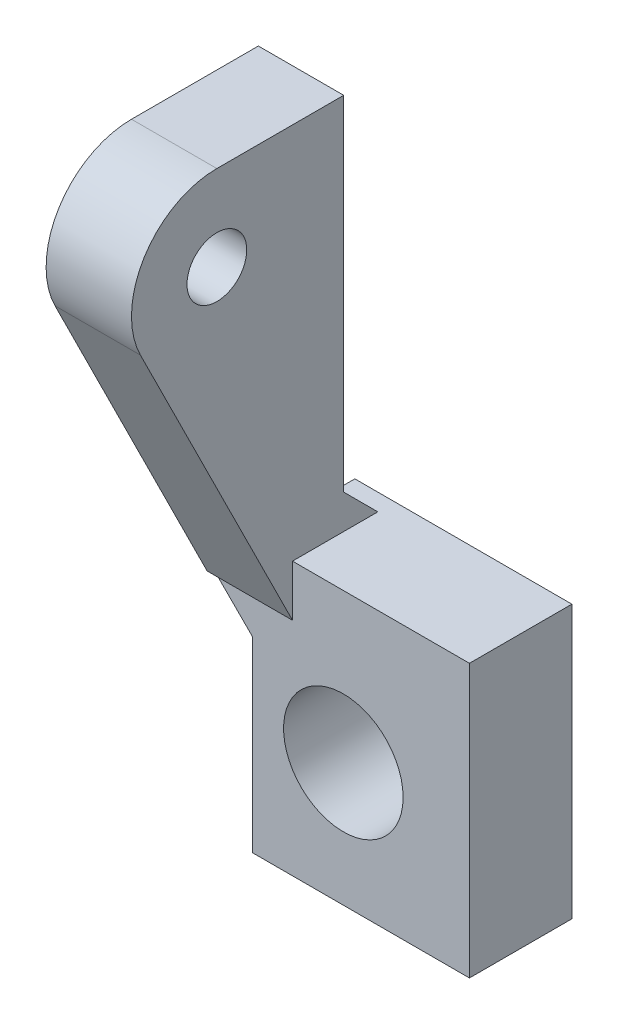
SolidWorks part; units mm, degrees
ref_plane "Front Plane" through (0, 0, 0) normal (0, 0, 1) x (1, 0, 0)
ref_plane "Top Plane" through (0, 0, 0) normal (0, 1, 0) x (1, 0, 0)
ref_plane "Right Plane" through (0, 0, 0) normal (1, 0, 0) x (0, 0, -1)
sketch "Sketch1" plane through (0, 0, 46.4115) normal (0, 0, 1) x (1, 0, 0)
  line L5 (33.1528, -0.655) -> (45.8638, -0.655)
  line L6 (33.1528, -0.655) -> (33.1528, 15.3086)
  line L7 (33.1528, 15.3086) -> (45.8638, 15.3086)
  line L8 (45.8638, -0.655) -> (45.8638, 15.3086)
  circle A0 centre (38.4789, 6.5666) radius 1.8 construction
  circle A1 centre (38.4789, 6.5666) radius 1.8
extrude "Boss-Extrude1" add sketch "Sketch1" along normal blind 1
sketch "Sketch2" plane through (30.5, 0, 0) normal (1, 0, 0) x (0, 0, -1)
  line L1 (-56.8415, 37.4376) -> (-49.4115, 37.4376)
  line L2 (-49.4115, 37.4376) -> (-49.4115, 17.3086)
  line L3 (-49.4115, 17.3086) -> (-47.4115, 15.3086)
  line L4 (-47.4115, 15.3086) -> (-47.4115, 12.3086)
  line L5 (-47.4115, -0.655) -> (-47.4115, 15.3086) construction
  line L6 (-47.4115, 12.3086) -> (-52.4115, 12.3086)
  line L7 (-52.4115, 12.3086) -> (-61.3181, 30.2104)
  arc A0 (-56.8415, 37.4376) -> (-61.3181, 30.2104) centre (-56.8415, 32.4376) ccw
  circle A1 centre (-56.8415, 32.4376) radius 1.75
  dimension "D1" = 10
  dimension "D2" = 45
  dimension "D3" = 2
  dimension "D4" = 5
  dimension "D5" = 3
extrude "Boss-Extrude2" add sketch "Sketch2" along normal blind 5
sketch "Sketch3" plane through (0, 0, 47.4115) normal (0, 0, 1) x (1, 0, 0)
  line L6 (35.5, 15.3086) -> (35.5, 12.3086)
  line L7 (35.5, 12.3086) -> (33.1528, 12.3086)
  line L8 (33.1528, 12.3086) -> (33.1528, -0.655)
  line L9 (33.1528, -0.655) -> (45.8638, -0.655)
  line L10 (45.8638, -0.655) -> (45.8638, 15.3086)
  line L11 (45.8638, 15.3086) -> (35.5, 15.3086)
  line L12 (35.5, 15.3086) -> (35.5, 12.3086)
  line L13 (35.5, 12.3086) -> (33.1528, 12.3086)
  line L14 (33.1528, 12.3086) -> (33.1528, -0.655)
  line L15 (33.1528, -0.655) -> (45.8638, -0.655)
  line L16 (45.8638, -0.655) -> (45.8638, 15.3086)
  line L17 (45.8638, 15.3086) -> (35.5, 15.3086)
  circle A0 centre (38.4789, 6.5666) radius 3.5
  dimension "D1" = 7
  dimension "D2" = 0
extrude "Boss-Extrude3" add sketch "Sketch3" along normal blind 5
chamfer "Chamfer1" distance 2 angle 45 1 edges at (33.1528, 12.3086, 49.9115)
